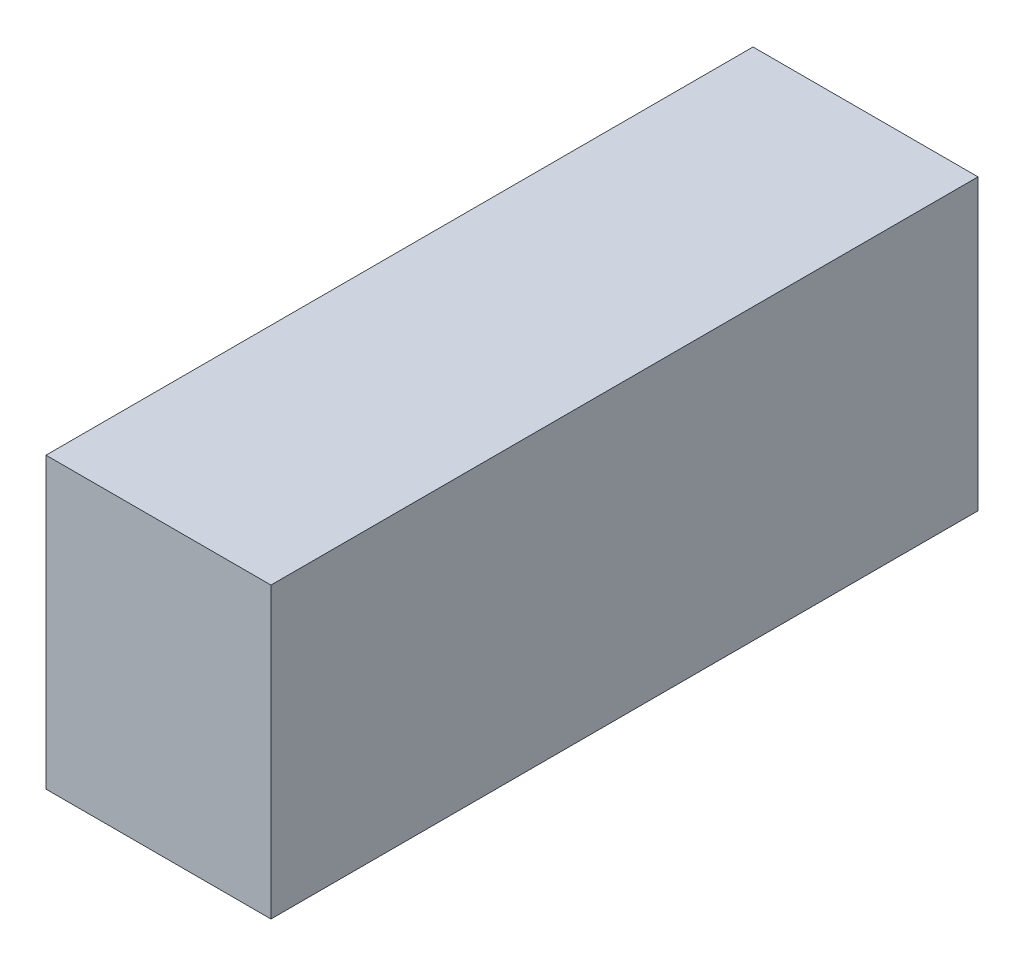
SolidWorks part; units mm, degrees
ref_plane "Front Plane" through (0, 0, 0) normal (0, 0, 1) x (1, 0, 0)
ref_plane "Top Plane" through (0, 0, 0) normal (0, 1, 0) x (1, 0, 0)
ref_plane "Right Plane" through (0, 0, 0) normal (1, 0, 0) x (0, 0, -1)
sketch "Sketch1" plane through (0, 0, 0) normal (0, 1, 0) x (1, 0, 0)
  line L1 (-22.225, 69.85) -> (22.225, 69.85)
  line L2 (-22.225, 69.85) -> (-22.225, -69.85)
  line L3 (-22.225, -69.85) -> (22.225, -69.85)
  line L4 (22.225, 69.85) -> (22.225, -69.85)
  point P4 (0, 69.85)
  point P6 (-22.225, 0)
  dimension "D1" = 44.45
  dimension "D2" = 139.7
extrude "Boss-Extrude1" add sketch "Sketch1" along normal blind 57.15
